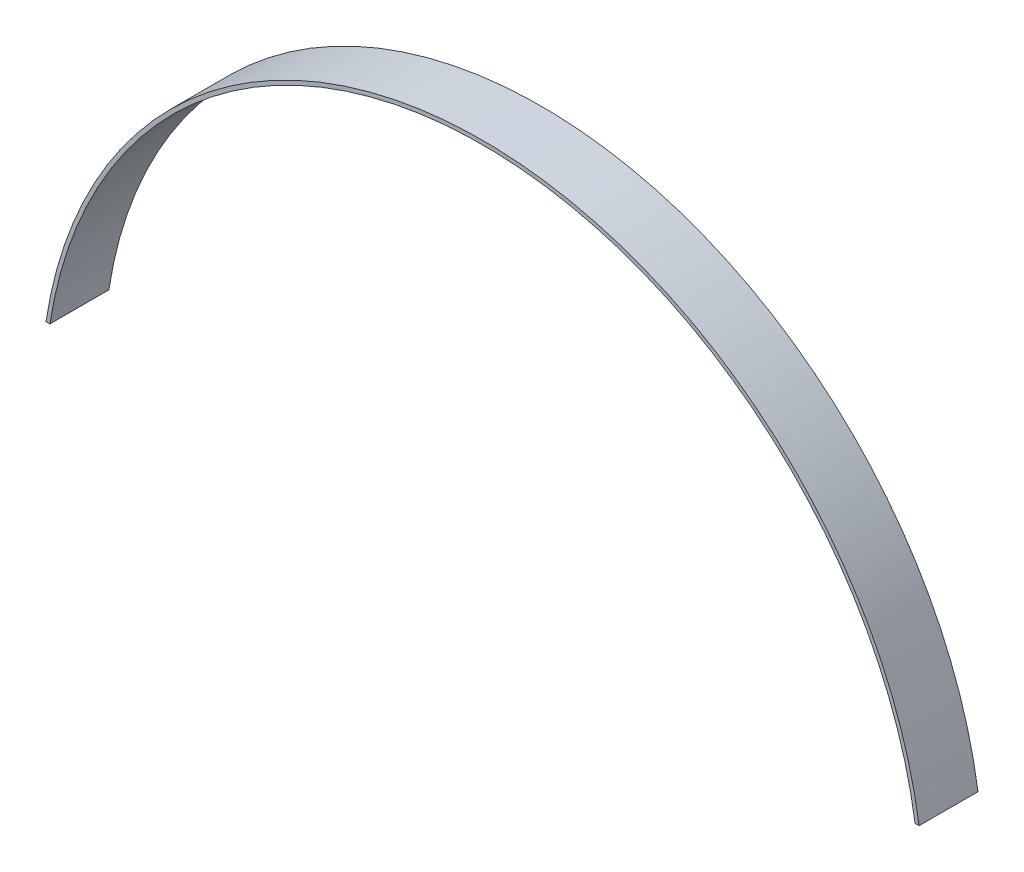
SolidWorks part; units mm, degrees
ref_plane "Front Plane" through (0, 0, 0) normal (0, 0, 1) x (1, 0, 0)
ref_plane "Top Plane" through (0, 0, 0) normal (0, 1, 0) x (1, 0, 0)
ref_plane "Right Plane" through (0, 0, 0) normal (1, 0, 0) x (0, 0, -1)
sketch "Sketch1" plane through (0, 0, 0) normal (0, 0, 1) x (1, 0, 0)
  line L0 (130.6753, -54.1538) -> (131.6868, -54.1538)
  line L1 (-90.6719, -54.1538) -> (-89.6603, -54.1538)
  arc A0 (131.6868, -54.1538) -> (-90.6719, -54.1538) centre (20.5075, -71.0109) ccw
  arc A1 (130.6753, -54.1538) -> (-89.6603, -54.1538) centre (20.5075, -71.0109) ccw
extrude "Boss-Extrude1" add sketch "Sketch1" along normal blind 15
